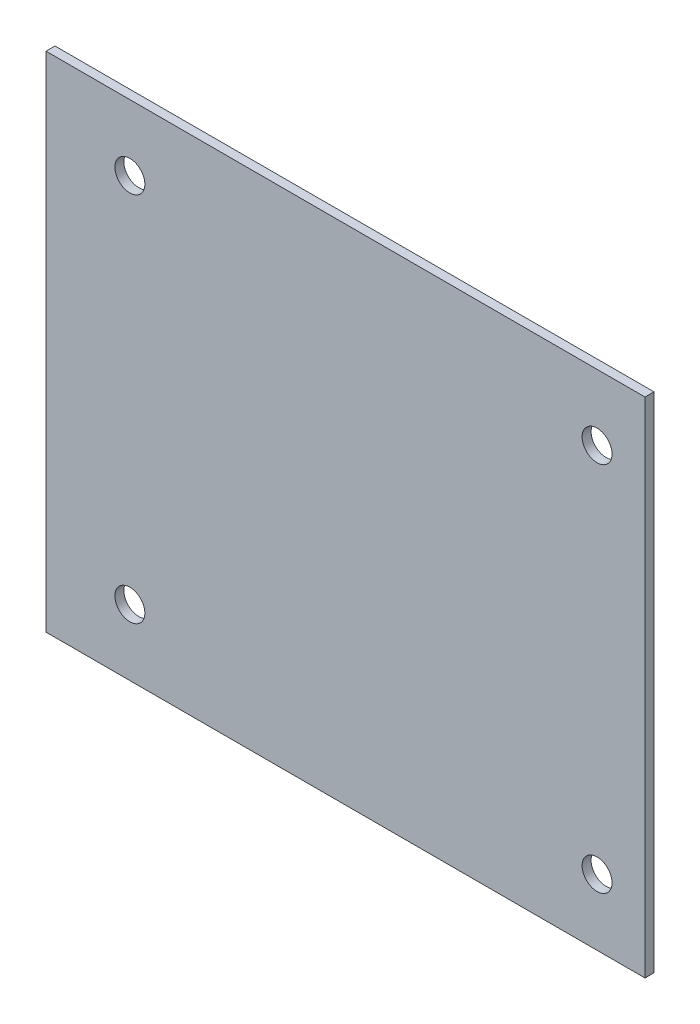
SolidWorks part; units mm, degrees
ref_plane "Front Plane" through (0, 0, 0) normal (0, 0, 1) x (1, 0, 0)
ref_plane "Top Plane" through (0, 0, 0) normal (0, 1, 0) x (1, 0, 0)
ref_plane "Right Plane" through (0, 0, 0) normal (1, 0, 0) x (0, 0, -1)
sketch "Sketch1" plane through (0, 0, 0) normal (0, 0, 1) x (1, 0, 0)
  line L1 (50, -42) -> (-50, -42)
  line L2 (50, -42) -> (50, 42)
  line L3 (50, 42) -> (-50, 42)
  line L4 (-50, -42) -> (-50, 42)
  line L5 (50, -42) -> (-50, 42) construction
  line L6 (50, 42) -> (-50, -42) construction
  line L7 (42, -31) -> (-36, -31)
  line L8 (42, -31) -> (42, 31)
  line L9 (42, 31) -> (-36, 31)
  line L10 (-36, -31) -> (-36, 31)
  line L11 (42, -31) -> (-36, 31) construction
  line L12 (42, 31) -> (-36, -31) construction
  circle A0 centre (-36, 31) radius 2.5
  circle A1 centre (42, 31) radius 2.5
  circle A2 centre (42, -31) radius 2.5
  circle A3 centre (-36, -31) radius 2.5
  point P0 (0, 0)
  point P6 (3, 0)
  dimension "D6" = 5
  dimension "D5" = 8
  dimension "D1" = 84
  dimension "D2" = 100
  dimension "D3" = 62
  dimension "D4" = 78
extrude "Boss-Extrude1" add sketch "Sketch1" along normal blind 1.5 contours L4 L1 L2 L3 A3 L10 A0 L9 A1 L8 A2 L7 | A3 L7 A2 L8 A1 L9 A0 L10
